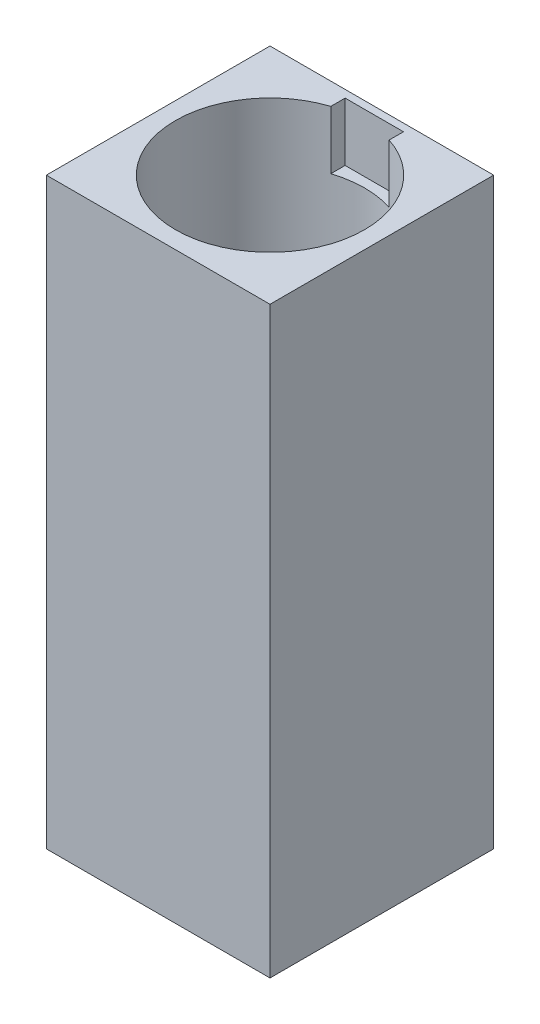
SolidWorks part; units mm, degrees
ref_plane "Front Plane" through (0, 0, 0) normal (1, 0, 0) x (0, 1, 0)
ref_plane "Top Plane" through (0, 0, 0) normal (0, 0, 1) x (0, 1, 0)
ref_plane "Right Plane" through (0, 0, 0) normal (0, 1, 0) x (-1, 0, 0)
sketch "Sketch1" plane through (0, 0, 0) normal (0, 1, 0) x (-1, 0, 0)
  line L1 (0, 0) -> (23, 0)
  line L2 (0, 0) -> (0, 23)
  line L3 (0, 23) -> (23, 23)
  line L4 (23, 0) -> (23, 23)
  dimension "D1" = 23
extrude "Boss-Extrude1" add sketch "Sketch1" along normal blind 60
sketch "Sketch2" plane through (0, 60, 0) normal (0, 1, 0) x (-1, 0, 0)
  circle A0 centre (11.5, 11.5) radius 9.725
  dimension "D1" = 19.45
extrude "Cut-Extrude1" cut sketch "Sketch2" against normal blind 39 contours A0
sketch "Sketch3" plane through (0, 21, 0) normal (0, 1, 0) x (-1, 0, 0)
  circle A0 centre (11.5, 11.5) radius 6.75
  dimension "D1" = 13.5
extrude "Cut-Extrude2" cut sketch "Sketch3" against normal through all contours A0
sketch "Sketch5" plane through (0, 60, 0) normal (0, 1, 0) x (-1, 0, 0)
  line L0 (11.5, 1.775) -> (11.5, 0.775) construction
  line L2 (8.5, 3.1737) -> (14.5, 3.1737)
  line L3 (8.5, 3.1737) -> (8.5, 0.775)
  line L4 (8.5, 0.775) -> (14.5, 0.775)
  line L5 (14.5, 3.1737) -> (14.5, 0.775)
  circle A0 centre (11.5, 11.5) radius 9.725 construction
  circle A1 centre (11.5, 11.5) radius 9.725 construction
  point P10 (11.5, 0.775)
  dimension "D1" = 1
  dimension "D2" = 6
  dimension "D3" = 2.3987
extrude "Cut-Extrude3" cut sketch "Sketch5" against normal blind 6 contours L3 L4 L5 L2
